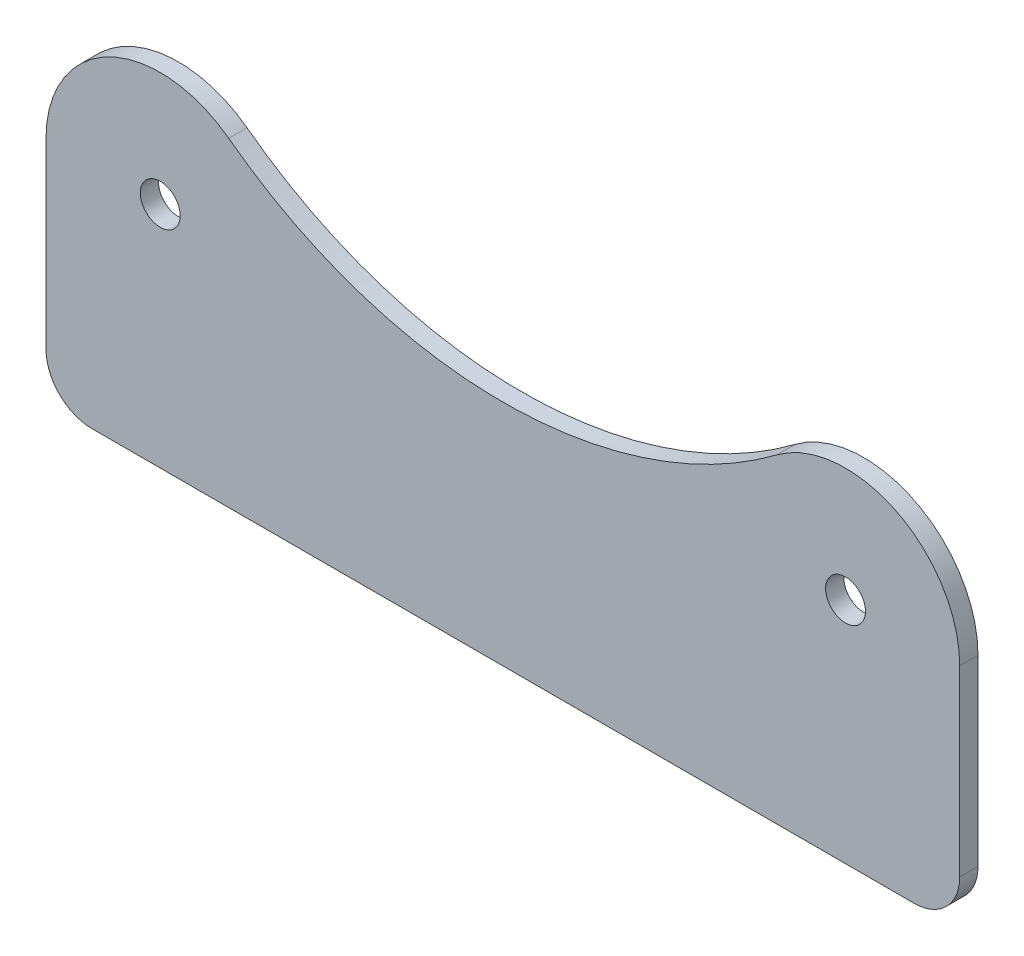
SolidWorks part; units mm, degrees
ref_plane "Front Plane" through (0, 0, 0) normal (0, 0, 1) x (1, 0, 0)
ref_plane "Top Plane" through (0, 0, 0) normal (0, 1, 0) x (1, 0, 0)
ref_plane "Right Plane" through (0, 0, 0) normal (1, 0, 0) x (0, 0, -1)
sketch "Sketch1" plane through (0, 0, 0) normal (0, 0, 1) x (1, 0, 0)
  line L0 (10, 0) -> (190, 0)
  line L1 (200, 10) -> (200, 50)
  line L2 (0, 50) -> (0, 10)
  line L3 (0, 0) -> (10, 0) construction
  line L4 (0, 0) -> (0, 10) construction
  circle A0 centre (25, 50) radius 4.3656
  circle A1 centre (175, 50) radius 4.3656
  arc A2 (0, 50) -> (40, 70) centre (25, 50) cw
  arc A3 (160, 70) -> (200, 50) centre (175, 50) cw
  arc A4 (160, 70) -> (40, 70) centre (100, 150) cw
  arc A5 (0, 10) -> (10, 0) centre (10, 10) ccw
  arc A6 (200, 10) -> (190, 0) centre (190, 10) cw
  point P28 (100, 0)
  dimension "D1" = 8.7312
  dimension "D3" = 25
  dimension "D4" = 10
  dimension "D5" = 100
  dimension "D2" = 150
  dimension "D6" = 50
extrude "Boss-Extrude1" add sketch "Sketch1" along normal blind 4
